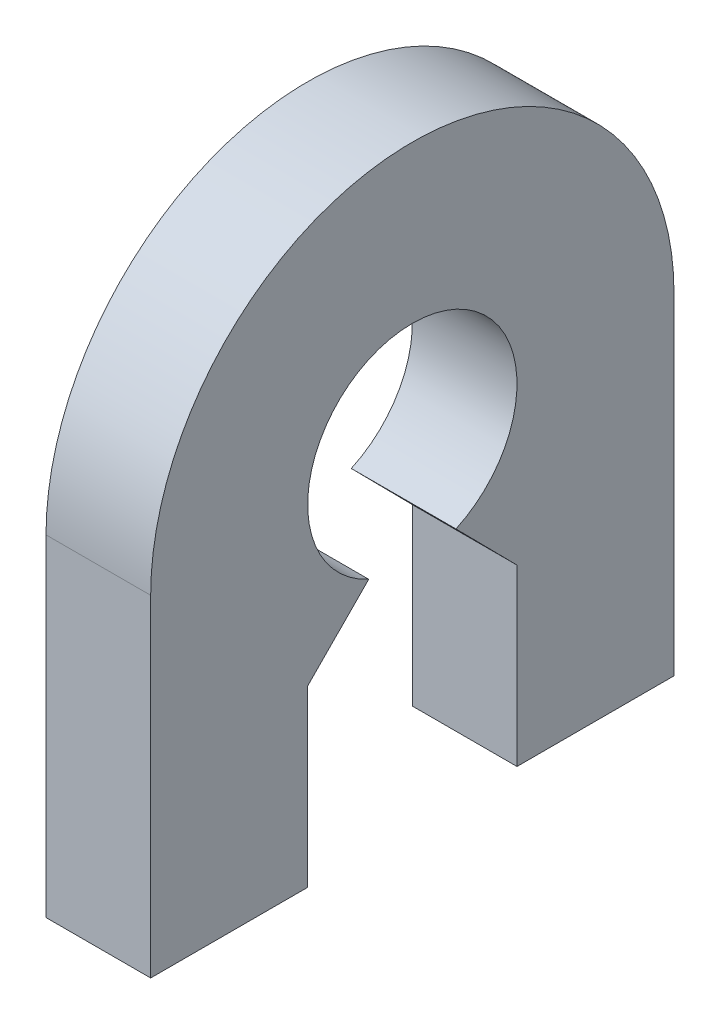
SolidWorks part; units mm, degrees
material "Резина"
ref_plane "Спереди" through (0, 0, 0) normal (0, 0, 1) x (1, 0, 0)
ref_plane "Сверху" through (0, 0, 0) normal (0, 1, 0) x (1, 0, 0)
ref_plane "Справа" through (0, 0, 0) normal (1, 0, 0) x (0, 0, -1)
other "Configuration Table"
sketch "Эскиз1" plane through (0, 0, 0) normal (1, 0, 0) x (0, 0, -1)
  point P0 (-1.3533, 16.0987)
  line B0 (15, 0) -> (15, 5)
  line B1 (15, 5) -> (6, 5)
  line B2 (6, 5) -> (6, 15)
  line B3 (6, 15) -> (2.5, 18.5456)
  line B4 (-2.5, 18.5456) -> (-6, 15)
  line B5 (-6, 15) -> (-6, 5)
  line B6 (-6, 5) -> (-15, 5)
  line B7 (-15, 5) -> (-15, 0)
  line B8 (-15, 0) -> (15, 0)
  arc B9 (2.5, 18.5456) -> (-2.5, 18.5456) centre (0, 24) ccw
sketch_block_instance "Блок1-1"
sketch_block "Блок1"
sketch "Эскиз2" plane through (0, 0, 0) normal (1, 0, 0) x (0, 0, -1)
  line L1 (15, 5) -> (6, 5) construction
  line L2 (6, 5) -> (6, 15) construction
  line L3 (6, 15) -> (2.5, 18.5456) construction
  line L4 (-2.5, 18.5456) -> (-6, 15) construction
  line L5 (-6, 15) -> (-6, 5) construction
  line L6 (-6, 5) -> (-15, 5) construction
  line L10 (15, 5) -> (6, 5)
  line L11 (6, 5) -> (6, 15)
  line L12 (6, 15) -> (2.5, 18.5456)
  line L13 (-2.5, 18.5456) -> (-6, 15)
  line L14 (-6, 15) -> (-6, 5)
  line L15 (-6, 5) -> (-15, 5)
  line L18 (-15, 5) -> (-15, 24)
  line L19 (15, 5) -> (15, 24)
  arc A0 (2.5, 18.5456) -> (-2.5, 18.5456) centre (0, 24) ccw construction
  arc A1 (2.5, 18.5456) -> (-2.5, 18.5456) centre (0, 24) ccw
  arc A2 (-15, 24) -> (15, 24) centre (0, 24) cw
extrude "Бобышка-Вытянуть1" add sketch "Эскиз2" along normal mid plane 6
